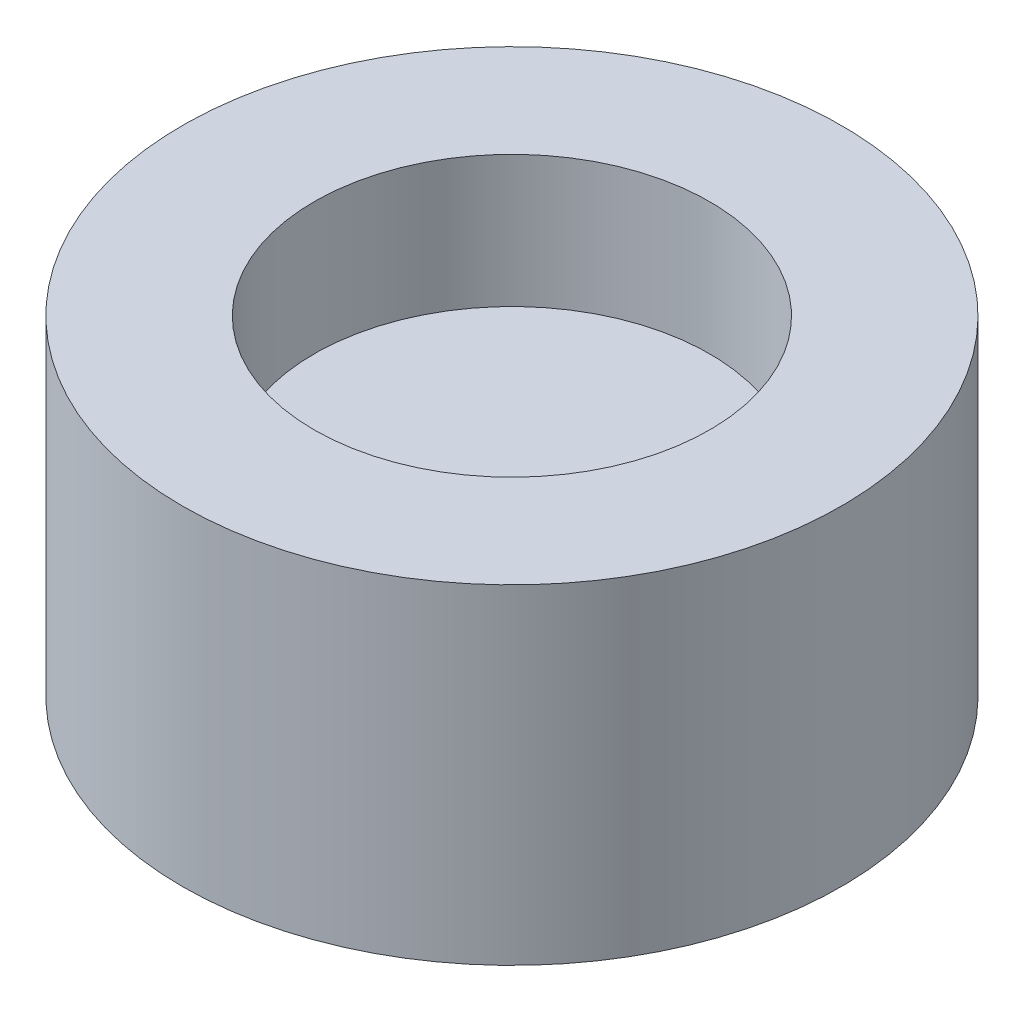
SolidWorks part; units mm, degrees
ref_plane "Front Plane" through (0, 0, 0) normal (0, 0, 1) x (1, 0, 0)
ref_plane "Top Plane" through (0, 0, 0) normal (0, 1, 0) x (1, 0, 0)
ref_plane "Right Plane" through (0, 0, 0) normal (1, 0, 0) x (0, 0, -1)
sketch "Sketch2" plane through (0, 0, 0) normal (0, 1, 0) x (1, 0, 0)
  circle A0 centre (0, 0) radius 2.5
  dimension "D1" = 5
extrude "Boss-Extrude1" add sketch "Sketch2" along normal blind 2.5
sketch "Sketch3" plane through (0, 2.5, 0) normal (0, 1, 0) x (1, 0, 0)
  circle A0 centre (0, 0) radius 1.5
  dimension "D1" = 3
extrude "Cut-Extrude1" cut sketch "Sketch3" against normal blind 1
